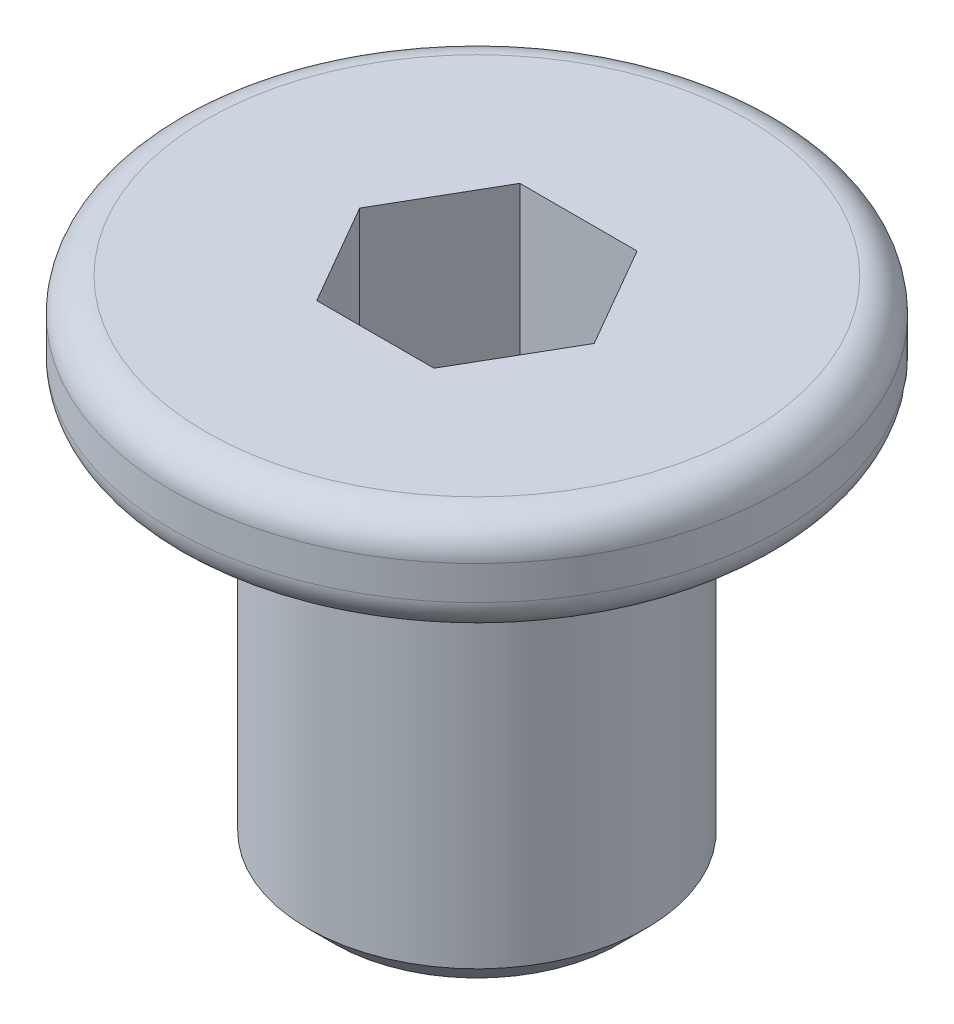
SolidWorks part; units mm, degrees
ref_plane "Front Plane" through (0, 0, 0) normal (0, 0, 1) x (1, 0, 0)
ref_plane "Top Plane" through (0, 0, 0) normal (0, 1, 0) x (1, 0, 0)
ref_plane "Right Plane" through (0, 0, 0) normal (1, 0, 0) x (0, 0, -1)
sketch "Sketch1" plane through (0, 0, 0) normal (0, 0, 1) x (1, 0, 0)
  line L1 (-4.5, -0.5) -> (-4.5, -1)
  line L2 (-4, -1.5) -> (-2.5, -1.5)
  line L3 (-2.5, -1.5) -> (-2.5, -7.1)
  line L5 (0, 2.75) -> (0, -11.9483) construction
  line L7 (-4, 0) -> (-1.5, 0)
  line L8 (-1.5, 0) -> (-1.5, -3)
  line L9 (-1.5, -3) -> (0, -4)
  line L10 (-2.1, -7.5) -> (0, -7.5)
  line L11 (-2.5, -7.1) -> (-2.1, -7.5)
  line L12 (0, -4) -> (0, -7.5)
  arc A1 (-4.5, -1) -> (-4, -1.5) centre (-4, -1) ccw
  arc A2 (-4, 0) -> (-4.5, -0.5) centre (-4, -0.5) ccw
  point P15 (-2.5, -7.5)
  dimension "D5" = 0.5
  dimension "D6" = 1.5
  dimension "D1" = 3
  dimension "D2" = 9
  dimension "D3" = 6
  dimension "D4" = 5
  dimension "D7" = 3
  dimension "D8" = 1
revolve "Revolve1" add sketch "Sketch1" angle 360 about L5
sketch "Sketch3" plane through (0, 0, 0) normal (0, 1, 0) x (1, 0, 0)
  line L1 (-0.866, -1.5) -> (0.866, -1.5)
  line L2 (0.866, -1.5) -> (1.7321, 0)
  line L3 (1.7321, 0) -> (0.866, 1.5)
  line L4 (0.866, 1.5) -> (-0.866, 1.5)
  line L5 (-0.866, 1.5) -> (-1.7321, 0)
  line L6 (-1.7321, 0) -> (-0.866, -1.5)
  circle A0 centre (0, 0) radius 1.5 construction
  circle A1 centre (0, 0) radius 1.5 construction
extrude "Cut-Extrude2" cut sketch "Sketch3" against normal blind 3
